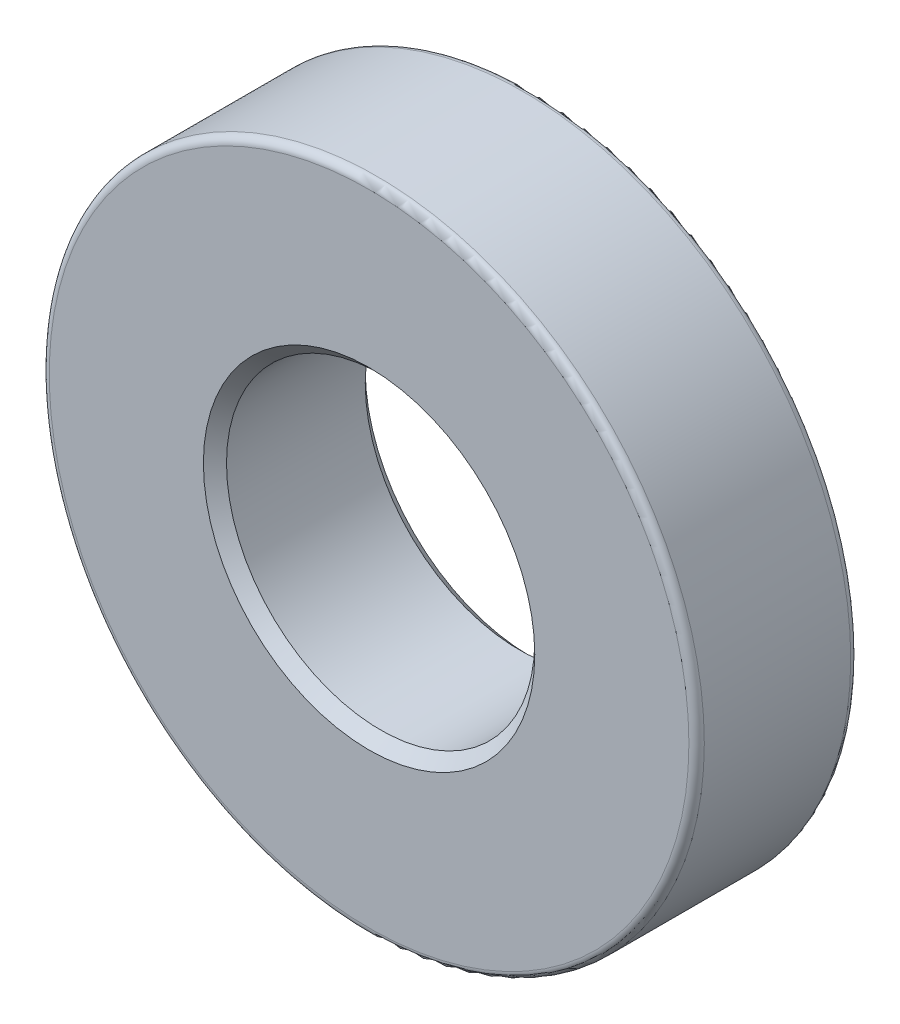
SolidWorks part; units mm, degrees
ref_plane "Front Plane" through (0, 0, 0) normal (0, 0, 1) x (1, 0, 0)
ref_plane "Top Plane" through (0, 0, 0) normal (0, 1, 0) x (1, 0, 0)
ref_plane "Right Plane" through (0, 0, 0) normal (1, 0, 0) x (0, 0, -1)
sketch "Sketch1" plane through (0, 0, 0) normal (0, 0, 1) x (1, 0, 0)
  circle A0 centre (0, 0) radius 8.5
  circle A1 centre (0, 0) radius 4
  dimension "D1" = 8
  dimension "D2" = 17
extrude "Boss-Extrude1" add sketch "Sketch1" along normal blind 4.2
chamfer "Chamfer1" distance 0.3 angle 45 2 edges at (4, 0, 4.2) (4, 0, 0)
fillet "Fillet1" radius 0.2 2 edges at (8.5, 0, 0) (8.5, 0, 4.2)
